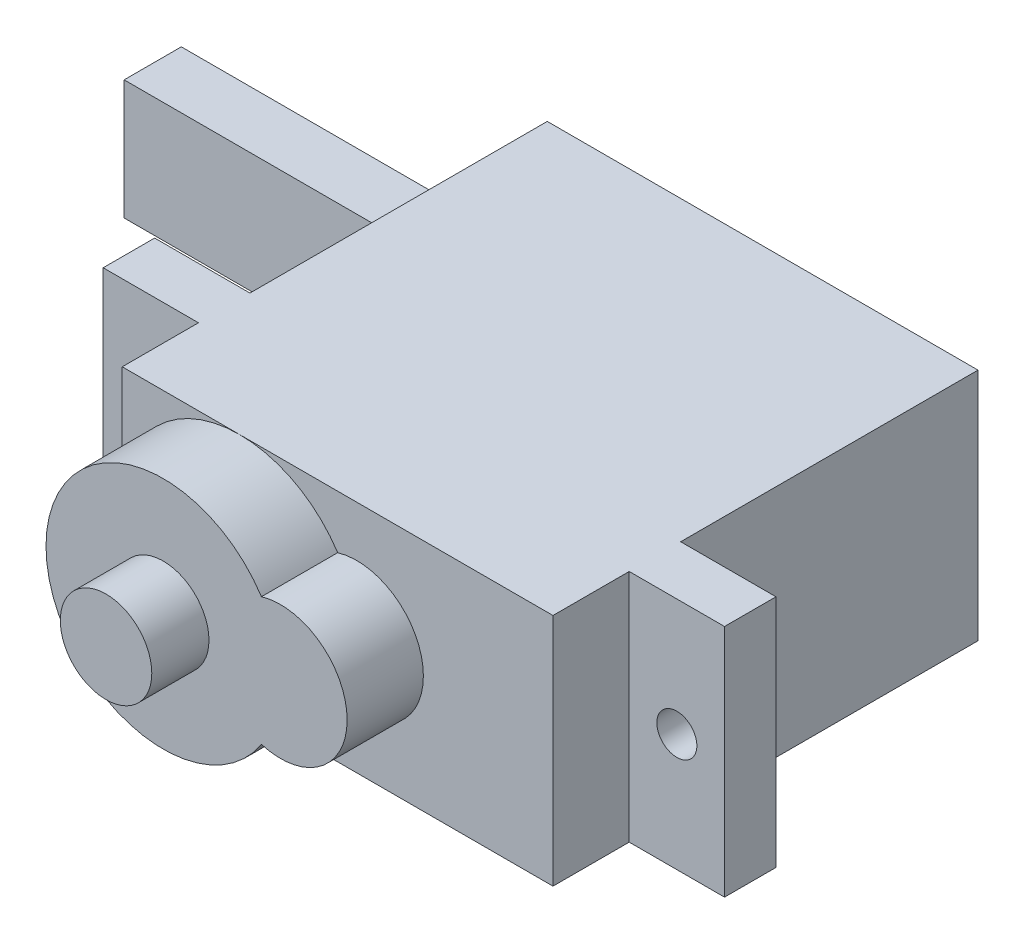
SolidWorks part; units mm, degrees
ref_plane "Plan de face" through (0, 0, 0) normal (0, 0, 1) x (1, 0, 0)
ref_plane "Plan de dessus" through (0, 0, 0) normal (0, 1, 0) x (1, 0, 0)
ref_plane "Plan de droite" through (0, 0, 0) normal (1, 0, 0) x (0, 0, -1)
sketch "Esquisse1" plane through (0, 0, 0) normal (0, 0, 1) x (1, 0, 0)
  line L1 (0, 0) -> (22.6, 0)
  line L2 (0, 0) -> (0, 12.3)
  line L3 (0, 12.3) -> (22.6, 12.3)
  line L4 (22.6, 0) -> (22.6, 12.3)
  dimension "D1" = 22.6
  dimension "D2" = 12.3
extrude "Boss.-Extru.1" add sketch "Esquisse1" along normal blind 22.3
sketch "Esquisse2" plane through (22.6, 0, 0) normal (1, 0, 0) x (0, 0, -1)
  line L0 (-15.6, 12.3) -> (-15.6, 0) construction
  line L1 (-22.3, 12.3) -> (0, 12.3) construction
  line L2 (-22.3, 0) -> (0, 0) construction
  line L3 (0, 12.3) -> (0, 0) construction
  line L4 (-18.3, 12.3) -> (-18.3, 0) construction
  line L5 (-22.3, 0) -> (-22.3, 12.3) construction
  line L7 (-18.3, 0) -> (-15.6, 0)
  line L8 (-18.3, 0) -> (-18.3, 12.3)
  line L9 (-18.3, 12.3) -> (-15.6, 12.3)
  line L10 (-15.6, 0) -> (-15.6, 12.3)
  dimension "D1" = 15.6
  dimension "D2" = 4
extrude "Boss.-Extru.2" add sketch "Esquisse2" along normal blind 5 and the other way blind 27.6
sketch "Esquisse3" plane through (0, 0, 18.3) normal (0, 0, 1) x (1, 0, 0)
  line L0 (27.6, 6.15) -> (-5, 6.15) construction
  line L1 (27.6, 12.3) -> (27.6, 0) construction
  line L2 (-5, 12.3) -> (-5, 0) construction
  line L3 (11.3, 6.15) -> (11.3, 12.3) construction
  line L4 (22.6, 12.3) -> (0, 12.3) construction
  line L5 (0, 6.15) -> (-5, 6.15) construction
  line L6 (0, 12.3) -> (0, 0) construction
  line L7 (-2.5, 6.15) -> (-2.5, 12.3) construction
  line L8 (-5, 12.3) -> (0, 12.3) construction
  circle A0 centre (-2.5, 6.15) radius 1.05
  circle A1 centre (25.1, 6.15) radius 1.05
extrude "Enlèv. mat.-Extru.1" cut sketch "Esquisse3" against normal blind 5
sketch "Esquisse4" plane through (0, 0, 22.3) normal (0, 0, 1) x (1, 0, 0)
  line L0 (0, 6.15) -> (22.6, 6.15) construction
  line L1 (0, 12.3) -> (0, 0) construction
  line L2 (22.6, 0) -> (22.6, 12.3) construction
  circle A0 centre (0, 6.15) radius 6.15 construction
  arc A1 (11.3041, 9.5053) -> (11.3041, 2.7947) centre (6.15, 6.15) ccw
  arc A2 (11.3041, 2.7947) -> (11.3041, 9.5053) centre (12.3, 6.15) ccw
extrude "Boss.-Extru.3" add sketch "Esquisse4" along normal blind 4
sketch "Esquisse5" plane through (0, 0, 26.3) normal (0, 0, 1) x (1, 0, 0)
  circle A0 centre (6.15, 6.15) radius 2.4
extrude "Boss.-Extru.4" add sketch "Esquisse5" along normal blind 3
sketch "Esquisse6" plane through (0, 0, 0) normal (-1, 0, 0) x (0, 0, 1)
  line L0 (6.2, 0) -> (6.2, 12.3) construction
  line L1 (15.6, 0) -> (0, 0) construction
  line L2 (15.6, 12.3) -> (0, 12.3) construction
  line L3 (15.6, 0) -> (15.6, 12.3) construction
  line L4 (3.2, 0) -> (3.2, 12.3) construction
  line L5 (6.2, 6.15) -> (3.2, 6.15) construction
  line L7 (6.2, 9.2889) -> (3.2, 9.2889)
  line L8 (6.2, 9.2889) -> (6.2, 3.0111)
  line L9 (6.2, 3.0111) -> (3.2, 3.0111)
  line L10 (3.2, 9.2889) -> (3.2, 3.0111)
  line L11 (6.2, 9.2889) -> (3.2, 3.0111) construction
  line L12 (6.2, 3.0111) -> (3.2, 9.2889) construction
  point P12 (4.7, 6.15)
  dimension "D1" = 9.4
  dimension "D2" = 3
extrude "Boss.-Extru.5" add sketch "Esquisse6" along normal blind 16
